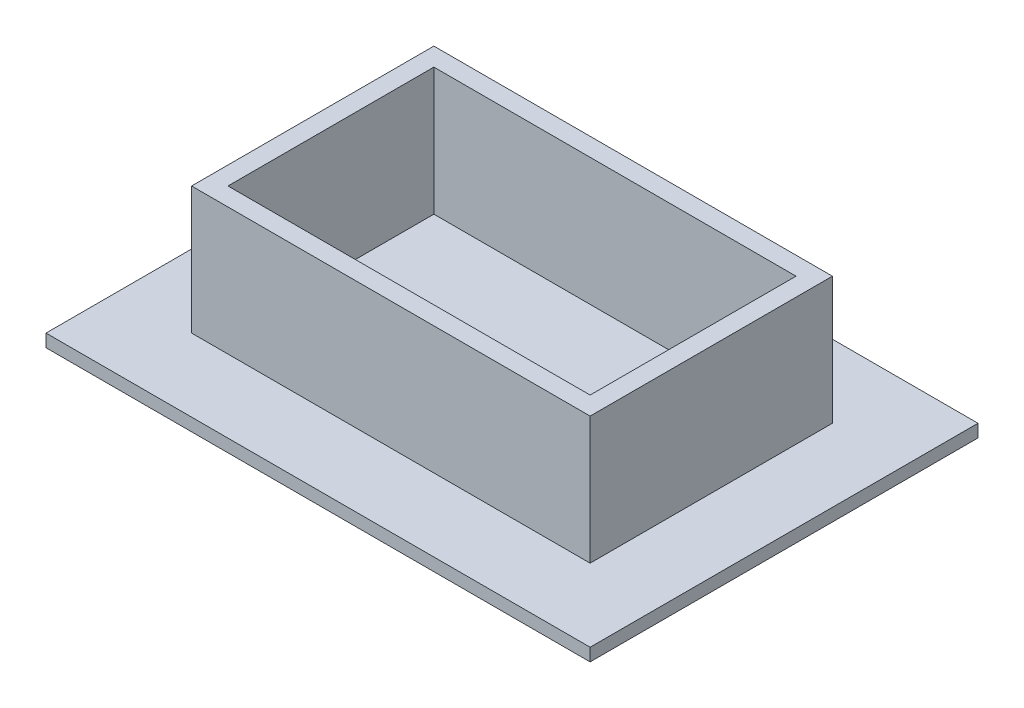
SolidWorks part; units mm, degrees
ref_plane "Front Plane" through (0, 0, 0) normal (0, 0, 1) x (1, 0, 0)
ref_plane "Top Plane" through (0, 0, 0) normal (0, 1, 0) x (1, 0, 0)
ref_plane "Right Plane" through (0, 0, 0) normal (1, 0, 0) x (0, 0, -1)
sketch "Sketch1" plane through (0, 0, 0) normal (0, 1, 0) x (1, 0, 0)
  line L1 (-37.9738, 27.0704) -> (37.9738, 27.0704)
  line L2 (-37.9738, 27.0704) -> (-37.9738, -27.0704)
  line L3 (-37.9738, -27.0704) -> (37.9738, -27.0704)
  line L4 (37.9738, 27.0704) -> (37.9738, -27.0704)
  line L5 (-37.9738, 27.0704) -> (37.9738, -27.0704) construction
  line L6 (-37.9738, -27.0704) -> (37.9738, 27.0704) construction
  point P0 (0, 0)
extrude "Boss-Extrude1" add sketch "Sketch1" along normal blind 1.778
sketch "Sketch2" plane through (0, 1.778, 0) normal (0, 1, 0) x (1, 0, 0)
  line L0 (-37.9738, 27.0704) -> (-37.9738, -27.0704) construction
  line L1 (-25.2738, -14.3704) -> (25.2738, -14.3704)
  line L2 (-25.2738, -14.3704) -> (-25.2738, 14.3704)
  line L3 (-25.2738, 14.3704) -> (25.2738, 14.3704)
  line L4 (25.2738, -14.3704) -> (25.2738, 14.3704)
  line L5 (-25.2738, -14.3704) -> (25.2738, 14.3704) construction
  line L6 (-25.2738, 14.3704) -> (25.2738, -14.3704) construction
  line L7 (-37.9738, -27.0704) -> (37.9738, -27.0704) construction
  line L8 (37.9738, -27.0704) -> (37.9738, 27.0704) construction
  line L9 (37.9738, 27.0704) -> (-37.9738, 27.0704) construction
  line L10 (-37.9738, 27.0704) -> (-37.9738, -27.0704)
  line L11 (-37.9738, -27.0704) -> (37.9738, -27.0704)
  line L12 (37.9738, -27.0704) -> (37.9738, 27.0704)
  line L13 (37.9738, 27.0704) -> (-37.9738, 27.0704)
  point P0 (0, 0)
  dimension "D1" = 12.7
  dimension "D2" = 12.7
extrude "Extrude-Thin1" add sketch "Sketch2" along normal blind 17.78 thin contours L2 L1 L4 L3
